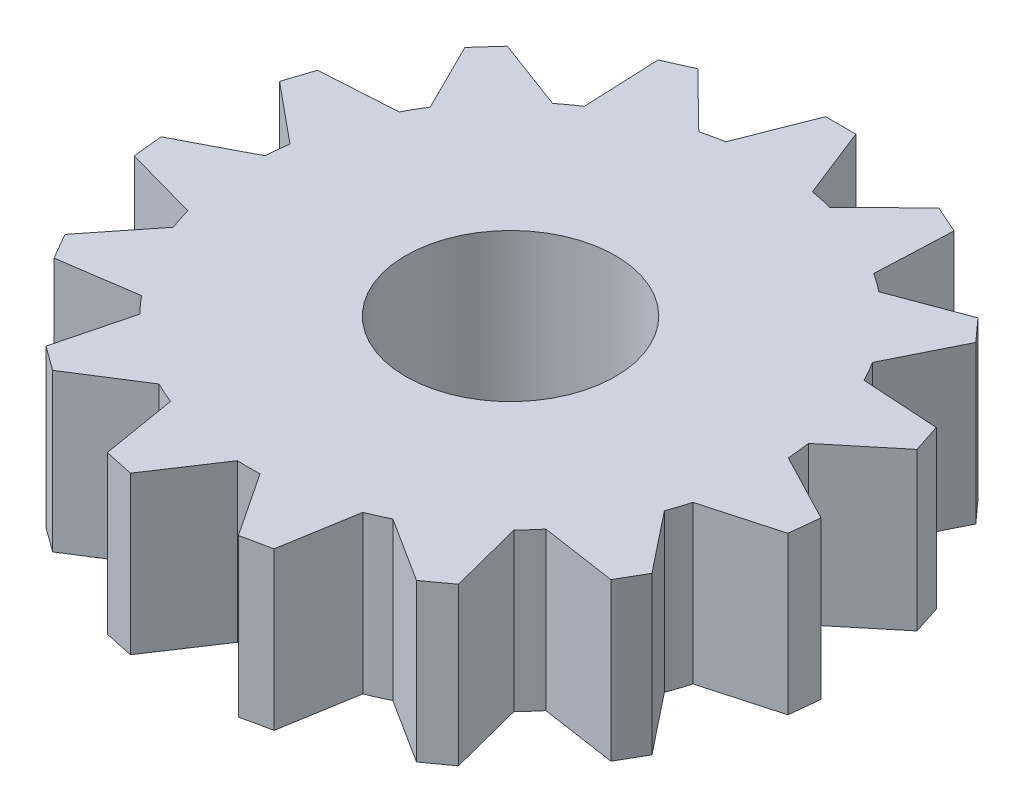
SolidWorks part; units mm, degrees
ref_plane "Front Plane" through (0, 0, 0) normal (0, 0, 1) x (1, 0, 0)
ref_plane "Top Plane" through (0, 0, 0) normal (0, 1, 0) x (1, 0, 0)
ref_plane "Right Plane" through (0, 0, 0) normal (1, 0, 0) x (0, 0, -1)
sketch "Sketch1" plane through (0, 0, 0) normal (0, 1, 0) x (1, 0, 0)
  line L0 (0, 0) -> (0, 4.0458) construction
  line L2 (-0.4136, 2.4655) -> (-0.1434, 3.1498)
  line L3 (0.4136, 2.4655) -> (0.1434, 3.1498)
  line L4 (-0.1434, 3.1498) -> (0.1434, 3.1498)
  line L5 (1.3807, 2.0842) -> (1.4121, 2.8191)
  line L6 (1.1501, 2.9358) -> (1.4121, 2.8191)
  line L7 (0.625, 2.4206) -> (1.1501, 2.9358)
  line L8 (2.109, 1.3424) -> (2.4367, 2.0011)
  line L9 (2.2448, 2.2142) -> (2.4367, 2.0011)
  line L10 (1.5555, 1.9571) -> (2.2448, 2.2142)
  line L11 (2.4727, 0.3685) -> (3.0399, 0.837)
  line L12 (2.9513, 1.1097) -> (3.0399, 0.837)
  line L13 (2.2171, 1.1553) -> (2.9513, 1.1097)
  line L14 (2.4088, -0.6691) -> (3.1175, -0.4718)
  line L15 (3.1475, -0.1866) -> (3.1175, -0.4718)
  line L16 (2.4953, 0.1536) -> (3.1475, -0.1866)
  line L17 (1.9284, -1.591) -> (2.6561, -1.6991)
  line L18 (2.7995, -1.4507) -> (2.6561, -1.6991)
  line L19 (2.342, -0.8746) -> (2.7995, -1.4507)
  line L20 (1.1146, -2.2378) -> (1.7354, -2.6325)
  line L21 (1.9674, -2.4639) -> (1.7354, -2.6325)
  line L22 (1.7838, -1.7516) -> (1.9674, -2.4639)
  line L23 (0.108, -2.4977) -> (0.5146, -3.1107)
  line L24 (0.7951, -3.0511) -> (0.5146, -3.1107)
  line L25 (0.9172, -2.3257) -> (0.7951, -3.0511)
  line L26 (-0.9172, -2.3257) -> (-0.7951, -3.0511)
  line L27 (-0.5146, -3.1107) -> (-0.7951, -3.0511)
  line L28 (-0.108, -2.4977) -> (-0.5146, -3.1107)
  line L29 (-1.7838, -1.7516) -> (-1.9674, -2.4639)
  line L30 (-1.7354, -2.6325) -> (-1.9674, -2.4639)
  line L31 (-1.1146, -2.2378) -> (-1.7354, -2.6325)
  line L32 (-2.342, -0.8746) -> (-2.7995, -1.4507)
  line L33 (-2.6561, -1.6991) -> (-2.7995, -1.4507)
  line L34 (-1.9284, -1.591) -> (-2.6561, -1.6991)
  line L35 (-2.4953, 0.1536) -> (-3.1475, -0.1866)
  line L36 (-3.1175, -0.4718) -> (-3.1475, -0.1866)
  line L37 (-2.4088, -0.6691) -> (-3.1175, -0.4718)
  line L38 (-2.2171, 1.1553) -> (-2.9513, 1.1097)
  line L39 (-3.0399, 0.837) -> (-2.9513, 1.1097)
  line L40 (-2.4727, 0.3685) -> (-3.0399, 0.837)
  line L41 (-1.5555, 1.9571) -> (-2.2448, 2.2142)
  line L42 (-2.4367, 2.0011) -> (-2.2448, 2.2142)
  line L43 (-2.109, 1.3424) -> (-2.4367, 2.0011)
  line L44 (-0.625, 2.4206) -> (-1.1501, 2.9358)
  line L45 (-1.4121, 2.8191) -> (-1.1501, 2.9358)
  line L46 (-1.3807, 2.0842) -> (-1.4121, 2.8191)
  arc A0 (-0.4136, 2.4655) -> (-0.625, 2.4206) centre (0, 0) ccw
  arc A1 (-1.3807, 2.0842) -> (-1.5555, 1.9571) centre (0, 0) ccw
  arc A2 (-2.109, 1.3424) -> (-2.2171, 1.1553) centre (0, 0) ccw
  arc A3 (-2.4727, 0.3685) -> (-2.4953, 0.1536) centre (0, 0) ccw
  arc A4 (0.625, 2.4206) -> (0.4136, 2.4655) centre (0, 0) ccw
  arc A5 (1.5555, 1.9571) -> (1.3807, 2.0842) centre (0, 0) ccw
  arc A6 (2.2171, 1.1553) -> (2.109, 1.3424) centre (0, 0) ccw
  arc A7 (2.4953, 0.1536) -> (2.4727, 0.3685) centre (0, 0) ccw
  arc A8 (2.342, -0.8746) -> (2.4088, -0.6691) centre (0, 0) ccw
  arc A9 (1.7838, -1.7516) -> (1.9284, -1.591) centre (0, 0) ccw
  arc A10 (0.9172, -2.3257) -> (1.1146, -2.2378) centre (0, 0) ccw
  arc A11 (-0.108, -2.4977) -> (0.108, -2.4977) centre (0, 0) ccw
  arc A12 (-1.1146, -2.2378) -> (-0.9172, -2.3257) centre (0, 0) ccw
  arc A13 (-1.9284, -1.591) -> (-1.7838, -1.7516) centre (0, 0) ccw
  arc A14 (-2.4088, -0.6691) -> (-2.342, -0.8746) centre (0, 0) ccw
  circle A15 centre (0, 0) radius 1
  point P1 (0, 3.1498)
  point P7 (0, 2.5)
  dimension "D1" = 5
  dimension "D2" = 0.6498
  dimension "D3" = 15
extrude "Boss-Extrude1" add sketch "Sketch1" along normal blind 1.5
